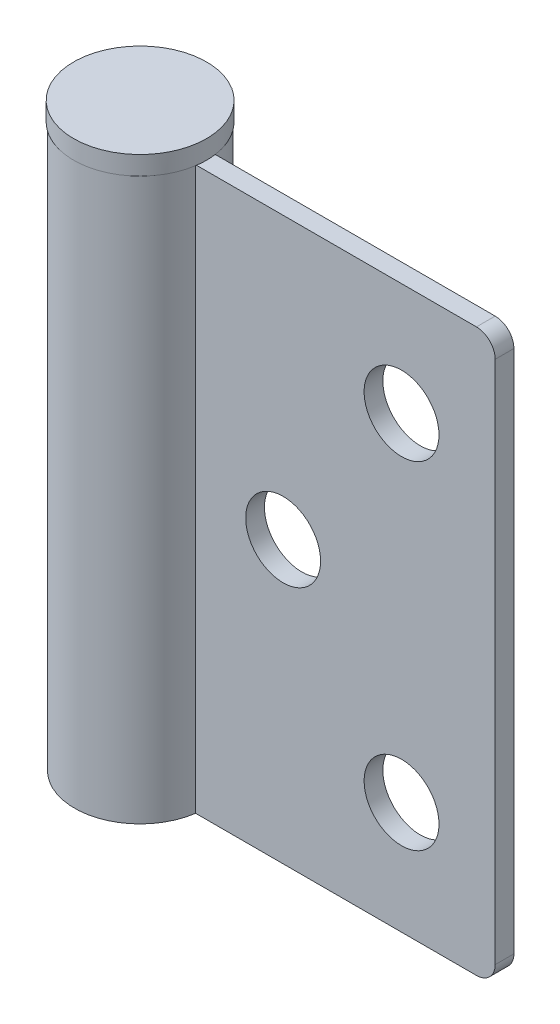
SolidWorks part; units mm, degrees
ref_plane "前视基准面" through (0, 0, 0) normal (0, 0, 1) x (1, 0, 0)
ref_plane "上视基准面" through (0, 0, 0) normal (0, 1, 0) x (1, 0, 0)
ref_plane "右视基准面" through (0, 0, 0) normal (1, 0, 0) x (0, 0, -1)
sketch "草图1" plane through (0, 0, 0) normal (0, 1, 0) x (1, 0, 0)
  line L0 (0, 0) -> (9.9203, 0) construction
  line L2 (19.4641, -0.5) -> (3.4641, -0.5)
  line L3 (19.4641, -0.5) -> (19.4641, 0.5)
  line L4 (19.4641, 0.5) -> (3.4641, 0.5)
  line L6 (19.4641, -0.5) -> (3.4641, 0.5) construction
  line L7 (19.4641, 0.5) -> (3.4641, -0.5) construction
  arc A0 (3.4641, 0.5) -> (3.4641, -0.5) centre (0, 0) ccw
  circle A1 centre (0, 0) radius 2.5
  point P4 (11.4641, 0)
  dimension "D2" = 7
  dimension "D4" = 5
  dimension "D1" = 1
  dimension "D3" = 16
extrude "凸台-拉伸1" add sketch "草图1" along normal blind 30
sketch "草图2" plane through (0, 0, 0.5) normal (0, 0, 1) x (1, 0, 0)
  line L0 (19.4641, 15) -> (3.4641, 15) construction
  line L1 (19.4641, 30) -> (19.4641, 0) construction
  line L2 (3.4641, 30) -> (3.4641, 0) construction
  circle A0 centre (14.4641, 24) radius 2
  circle A1 centre (8.1395, 15) radius 2
  circle A2 centre (14.4641, 6) radius 2
  dimension "D1" = 4
  dimension "D5" = 4
  dimension "D2" = 18
  dimension "D3" = 11
  dimension "D4" = 5
extrude "切除-拉伸1" cut sketch "草图2" against normal up to next
fillet "圆角1" radius 1 2 edges at (19.4641, 30, 0) (19.4641, 0, 0)
sketch "草图3" plane through (0, 30, 0) normal (0, 1, 0) x (1, 0, 0)
  circle A0 centre (0, 0) radius 3.55
  dimension "D1" = 7.1
extrude "凸台-拉伸2" add sketch "草图3" along normal blind 1
